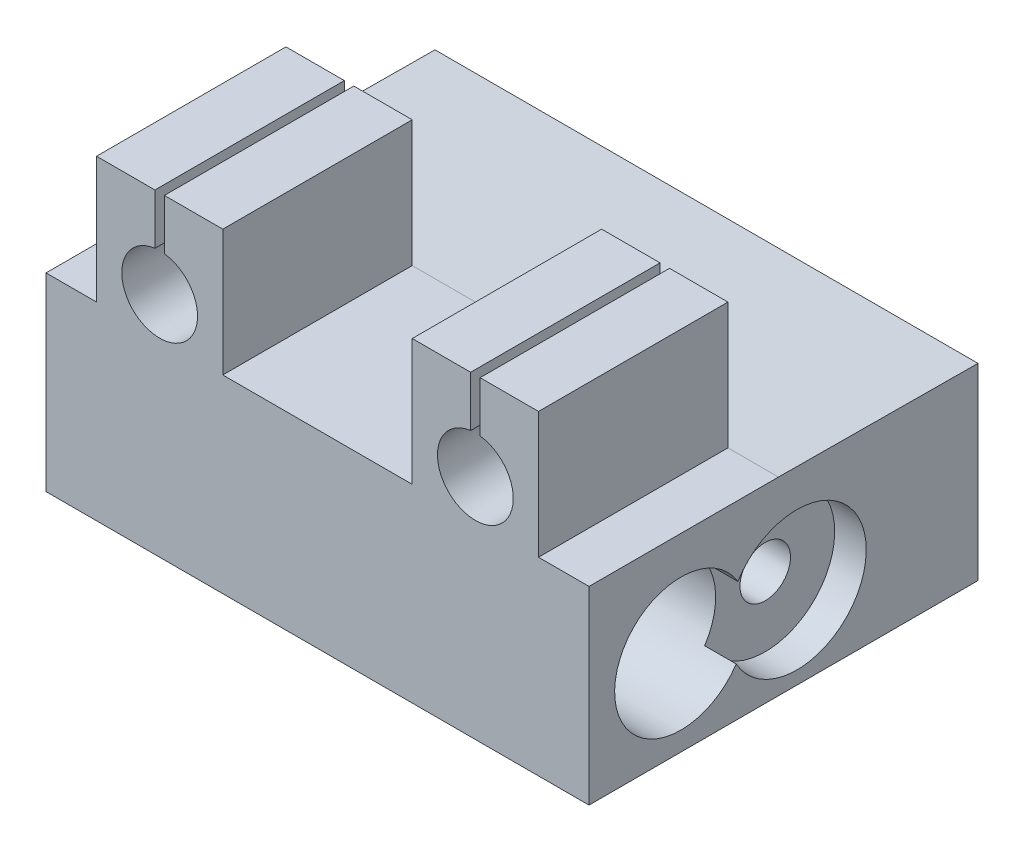
SolidWorks part; units mm, degrees
ref_plane "Спереди" through (0, 0, 0) normal (0, 0, 1) x (1, 0, 0)
ref_plane "Сверху" through (0, 0, 0) normal (0, 1, 0) x (1, 0, 0)
ref_plane "Справа" through (0, 0, 0) normal (1, 0, 0) x (0, 0, -1)
sketch "Эскиз1" plane through (0, 0, 0) normal (0, 0, 1) x (1, 0, 0)
  line L0 (0, 26.4403) -> (0, -13.9347) construction
  line L1 (-19.8247, 0) -> (22.9277, 0) construction
  line L2 (-43, 0) -> (-43, 30)
  line L3 (-43, 30) -> (-35, 30)
  line L4 (-35, 30) -> (-35, 50)
  line L5 (-35, 50) -> (-25.75, 50)
  line L6 (-15, 50) -> (-15, 30)
  line L7 (-15, 30) -> (0, 30)
  line L8 (0, 30) -> (15, 30)
  line L9 (15, 30) -> (15, 50)
  line L10 (-15, 50) -> (-24.25, 50)
  line L11 (35, 50) -> (35, 30)
  line L12 (35, 30) -> (43, 30)
  line L13 (43, 30) -> (43, 0)
  line L14 (43, 0) -> (0, 0)
  line L15 (0, 0) -> (-43, 0)
  line L16 (15, 50) -> (24.25, 50)
  line L17 (35, 50) -> (25.75, 50)
  line L18 (-25.75, 50) -> (-25.75, 42)
  line L19 (-24.25, 50) -> (-24.25, 42)
  line L20 (24.25, 50) -> (24.25, 42)
  line L21 (25.75, 50) -> (25.75, 42)
  line L22 (-25, 36.0471) -> (25, 36.0471) construction
  arc A0 (-24.25, 42) -> (-25.75, 42) centre (-25, 36.0471) cw
  arc A1 (25.75, 42) -> (24.25, 42) centre (25, 36.0471) cw
  point P29 (0, 26.4403)
  point P30 (-14.746, 11.5772)
  point P31 (0, 0)
  point P32 (0, 0)
  point P33 (16.208, 11.6648)
  dimension "D2" = 6
  dimension "D1" = 1.5
  dimension "D3" = 30
  dimension "D4" = 8
  dimension "D5" = 20
  dimension "D6" = 20
  dimension "D7" = 8
  dimension "D8" = 30
  dimension "D9" = 50
extrude "Бобышка-Вытянуть1" add sketch "Эскиз1" along normal blind 30
sketch "Эскиз2" plane through (-43, 0, 0) normal (-1, 0, 0) x (0, 0, 1)
  circle A0 centre (15.4453, 13.5119) radius 10.5
  dimension "D1" = 21
extrude "Вырез-Вытянуть1" cut sketch "Эскиз2" against normal through all
sketch "Эскиз4" plane through (43, 0, 0) normal (1, 0, 0) x (0, 0, -1)
  line L0 (0, 0) -> (31.6003, 0)
  line L1 (31.6003, 0) -> (31.6003, 29.7919)
  line L2 (31.6003, 29.7919) -> (0, 30)
  line L3 (0, 30) -> (0, 0)
extrude "Бобышка-Вытянуть3" add sketch "Эскиз4" against normal up to vertex (86 mm away)
sketch "Эскиз5" plane through (-43, 0, 0) normal (-1, 0, 0) x (0, 0, 1)
  circle A1 centre (-2.9058, 13.0793) radius 4
  point P1 (0, 0)
  point P3 (-2.9058, 13.0793)
  dimension "D2" = 8
extrude "Вырез-Вытянуть3" cut sketch "Эскиз5" against normal up to surface (86 mm away) up to face at (43, 13.5119, 25.9453)
sketch "Эскиз6" plane through (-43, 0, 0) normal (-1, 0, 0) x (0, 0, 1)
  circle A0 centre (-2.9058, 13.0793) radius 11
  dimension "D1" = 22
extrude "Вырез-Вытянуть4" cut sketch "Эскиз6" against normal blind 5
sketch "Эскиз7" plane through (43, 0, 0) normal (1, 0, 0) x (0, 0, -1)
  circle A0 centre (2.9058, 13.0793) radius 11
  dimension "D1" = 22
extrude "Вырез-Вытянуть5" cut sketch "Эскиз7" against normal blind 5
